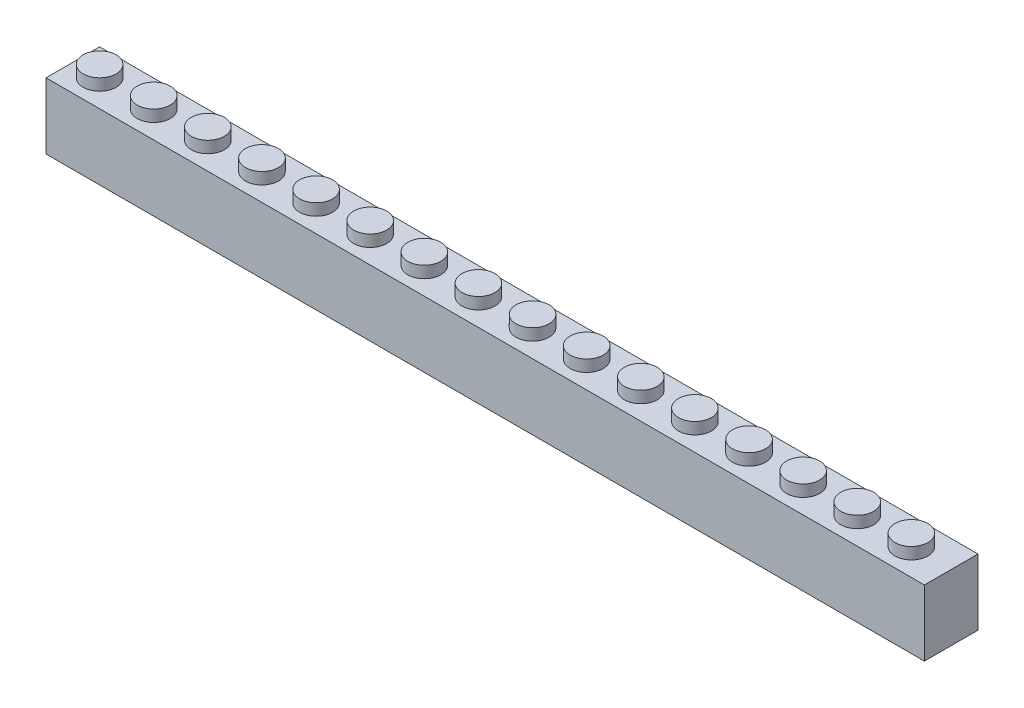
SolidWorks part; units mm, degrees
ref_plane "Спереди" through (0, 0, 0) normal (0, 0, 1) x (1, 0, 0)
ref_plane "Сверху" through (0, 0, 0) normal (0, 1, 0) x (1, 0, 0)
ref_plane "Справа" through (0, 0, 0) normal (1, 0, 0) x (0, 0, -1)
sketch "Эскиз1" plane through (0, 0, 0) normal (0, 1, 0) x (1, 0, 0)
  line L1 (63.9, -3.9) -> (-63.9, -3.9)
  line L2 (63.9, -3.9) -> (63.9, 3.9)
  line L3 (63.9, 3.9) -> (-63.9, 3.9)
  line L4 (-63.9, -3.9) -> (-63.9, 3.9)
  line L5 (63.9, -3.9) -> (-63.9, 3.9) construction
  line L6 (63.9, 3.9) -> (-63.9, -3.9) construction
  circle A0 centre (-60, 0) radius 2.4
  circle A1 centre (-52.126, 0) radius 2.4
  circle A2 centre (-44.252, 0) radius 2.4
  circle A3 centre (-36.378, 0) radius 2.4
  circle A4 centre (-28.504, 0) radius 2.4
  circle A5 centre (-20.63, 0) radius 2.4
  circle A6 centre (-12.756, 0) radius 2.4
  circle A7 centre (-4.882, 0) radius 2.4
  circle A8 centre (2.992, 0) radius 2.4
  circle A9 centre (10.866, 0) radius 2.4
  circle A10 centre (18.74, 0) radius 2.4
  circle A11 centre (26.614, 0) radius 2.4
  circle A12 centre (34.488, 0) radius 2.4
  circle A13 centre (42.362, 0) radius 2.4
  circle A14 centre (50.236, 0) radius 2.4
  circle A15 centre (58.11, 0) radius 2.4
  point P0 (0, 0)
  dimension "D3" = 3.9
  dimension "D1" = 127.8
  dimension "D2" = 7.8
  dimension "D4" = 3.9
  dimension "D5" = 16
extrude "Бобышка-Вытянуть1" add sketch "Эскиз1" along normal blind 9.6 contours L2 L1 L4 L3
sketch "Эскиз2" plane through (0, 9.6, 0) normal (0, 1, 0) x (1, 0, 0)
  line L0 (-63.9, -3.9) -> (-63.9, 3.9) construction
  circle A0 centre (-60, 0) radius 2.4
  circle A1 centre (-52.126, 0) radius 2.4
  circle A2 centre (-44.252, 0) radius 2.4
  circle A3 centre (-36.378, 0) radius 2.4
  circle A4 centre (-28.504, 0) radius 2.4
  circle A5 centre (-20.63, 0) radius 2.4
  circle A6 centre (-12.756, 0) radius 2.4
  circle A7 centre (-4.882, 0) radius 2.4
  circle A8 centre (2.992, 0) radius 2.4
  circle A9 centre (10.866, 0) radius 2.4
  circle A10 centre (18.74, 0) radius 2.4
  circle A11 centre (26.614, 0) radius 2.4
  circle A12 centre (34.488, 0) radius 2.4
  circle A13 centre (42.362, 0) radius 2.4
  circle A14 centre (50.236, 0) radius 2.4
  circle A15 centre (58.11, 0) radius 2.4
  dimension "D1" = 3.9
  dimension "D2" = 16
extrude "Бобышка-Вытянуть2" add sketch "Эскиз2" along normal blind 1.7
sketch "Эскиз3" plane through (0, 0, 0) normal (0, -1, 0) x (1, 0, 0)
  line L0 (-63.9, 3.9) -> (-63.9, -3.9) construction
  line L1 (63.9, -3.9) -> (-63.9, -3.9) construction
  circle A0 centre (-60, 0) radius 2.5
  circle A1 centre (-52.126, 0) radius 2.5
  circle A2 centre (-44.252, 0) radius 2.5
  circle A3 centre (-36.378, 0) radius 2.5
  circle A4 centre (-28.504, 0) radius 2.5
  circle A5 centre (-20.63, 0) radius 2.5
  circle A6 centre (-12.756, 0) radius 2.5
  circle A7 centre (-4.882, 0) radius 2.5
  circle A8 centre (2.992, 0) radius 2.5
  circle A9 centre (10.866, 0) radius 2.5
  circle A10 centre (18.74, 0) radius 2.5
  circle A11 centre (26.614, 0) radius 2.5
  circle A12 centre (34.488, 0) radius 2.5
  circle A13 centre (42.362, 0) radius 2.5
  circle A14 centre (50.236, 0) radius 2.5
  circle A15 centre (58.11, 0) radius 2.5
  dimension "D1" = 3.9
  dimension "D3" = 16
  dimension "D2" = 3.9
extrude "Вырез-Вытянуть2" cut sketch "Эскиз3" against normal blind 1.8
